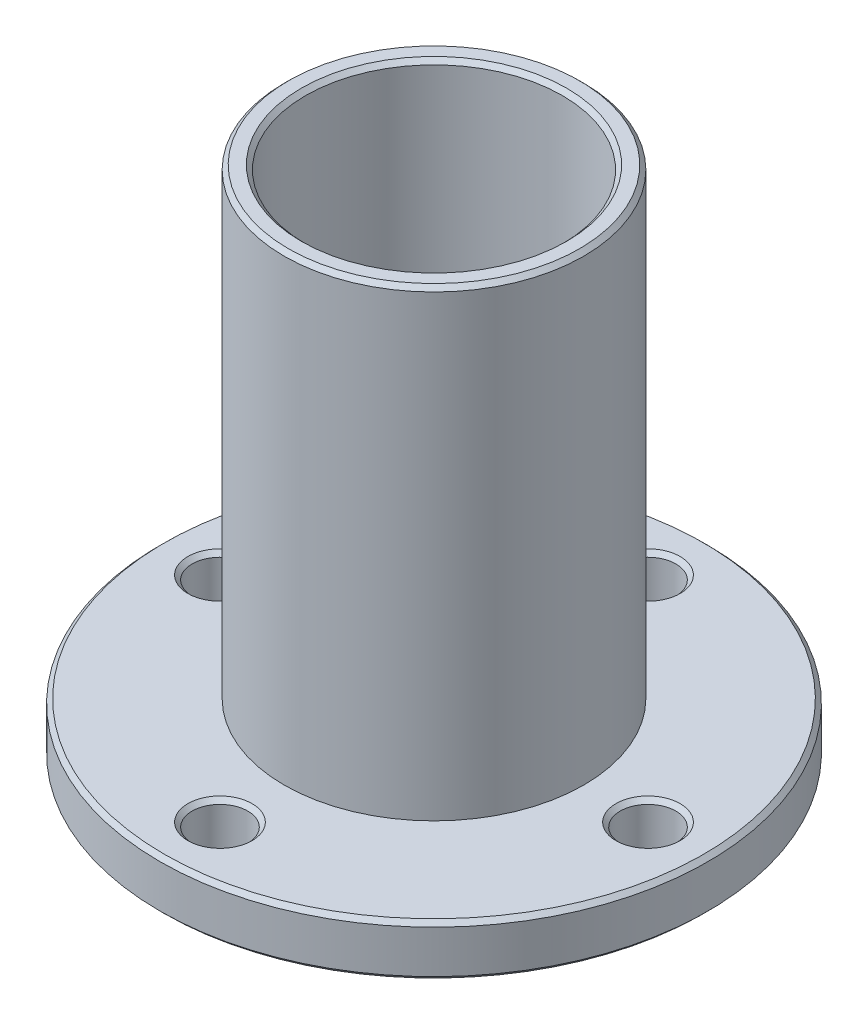
SolidWorks part; units mm, degrees
ref_plane "Front Plane" through (0, 0, 0) normal (0, 0, 1) x (1, 0, 0)
ref_plane "Top Plane" through (0, 0, 0) normal (0, 1, 0) x (1, 0, 0)
ref_plane "Right Plane" through (0, 0, 0) normal (1, 0, 0) x (0, 0, -1)
sketch "Sketch1" plane through (0, 0, 0) normal (0, 1, 0) x (1, 0, 0)
  circle A0 centre (0, 0) radius 32
  dimension "D1" = 64
extrude "Boss-Extrude1" add sketch "Sketch1" along normal blind 60
sketch "Sketch2" plane through (0, 60, 0) normal (0, 1, 0) x (1, 0, 0)
  circle A0 centre (0, 0) radius 17.5
  dimension "D1" = 35
extrude "Cut-Extrude1" cut sketch "Sketch2" against normal blind 54 flip side to cut
sketch "Sketch4" plane through (0, 0, 0) normal (0, -1, 0) x (1, 0, 0)
  circle A0 centre (0, 0) radius 20
  dimension "D1" = 40
extrude "Cut-Extrude2" cut sketch "Sketch4" against normal blind 2.3
sketch "Sketch5" plane through (0, 2.3, 0) normal (0, -1, 0) x (1, 0, 0)
  circle A0 centre (0, 0) radius 15
  dimension "D1" = 30
extrude "Cut-Extrude3" cut sketch "Sketch5" against normal through all
chamfer "Chamfer1" distance 0.5 angle 45 5 edges at (0, 2.3, -15) (0, 60, -15) (0, 60, 17.5) (0, 6, 32) (0, 0, 32)
sketch "Sketch6" plane through (0, 0, 0) normal (0, -1, 0) x (1, 0, 0)
  circle A6 centre (25, 0) radius 3.25
  circle A7 centre (0, -25) radius 3.25
  circle A8 centre (-25, 0) radius 3.25
  circle A9 centre (0, 25) radius 3.25
  dimension "D2" = 6.5
  dimension "D3" = 6.5
  dimension "D4" = 6.5
  dimension "D5" = 6.5
extrude "Cut-Extrude4" cut sketch "Sketch6" against normal through all
chamfer "Chamfer2" distance 0.5 angle 45 8 edges at (0, 6, -21.75) (-25, 6, 3.25) (0, 0, -28.25) (-25, 0, -3.25) (0, 0, 21.75) (0, 6, 28.25) (25, 6, 3.25) (25, 0, -3.25)
